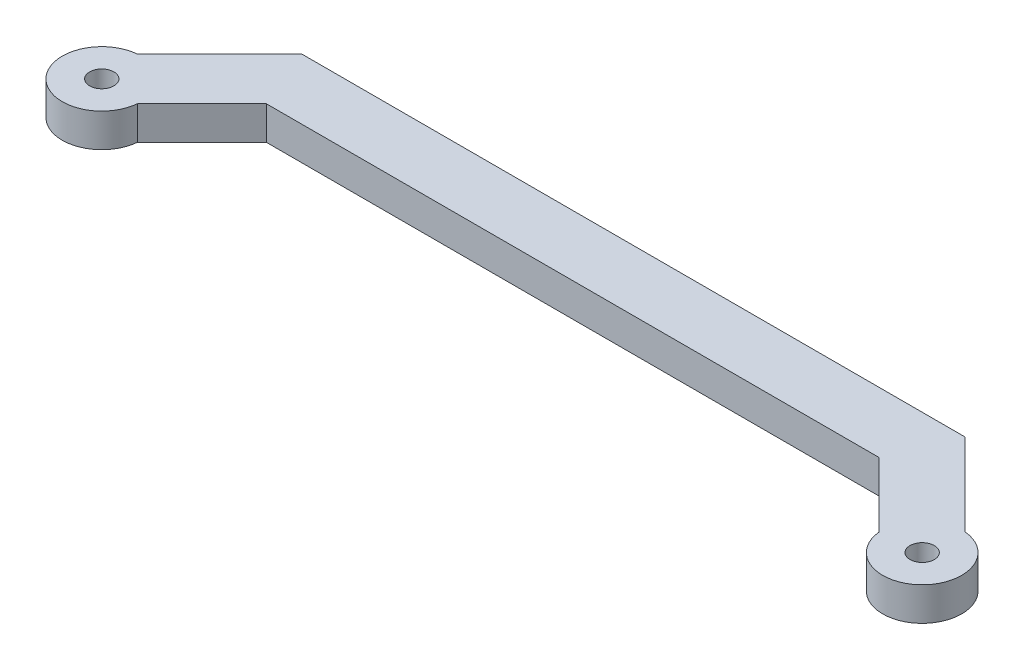
SolidWorks part; units mm, degrees
ref_plane "Plan de face" through (0, 0, 0) normal (0, 0, 1) x (1, 0, 0)
ref_plane "Plan de dessus" through (0, 0, 0) normal (0, 1, 0) x (1, 0, 0)
ref_plane "Plan de droite" through (0, 0, 0) normal (1, 0, 0) x (0, 0, -1)
sketch "Sketch1" plane through (0, 0, 0) normal (0, 1, 0) x (1, 0, 0)
  line L0 (67.5, -10) -> (52.5, 5) construction
  line L1 (52.5, 5) -> (-52.5, 5) construction
  line L2 (0, 5) -> (0, 0) construction
  line L3 (-50.4289, 0) -> (50.4289, 0)
  line L5 (54.5711, 10) -> (-54.5711, 10)
  line L6 (0, 5) -> (0, 0)
  line L7 (50.4289, 0) -> (61.0276, -10.5987)
  line L8 (54.5711, 10) -> (68.0987, -3.5276)
  line L9 (-67.5, -10) -> (-52.5, 5) construction
  line L10 (-54.5711, 10) -> (-68.0987, -3.5276)
  line L11 (-50.4289, 0) -> (-61.0276, -10.5987)
  arc A0 (61.0276, -10.5987) -> (68.0987, -3.5276) centre (67.5, -10) ccw
  circle A1 centre (67.5, -10) radius 2
  circle A2 centre (-67.5, -10) radius 2
  arc A3 (-61.0276, -10.5987) -> (-68.0987, -3.5276) centre (-67.5, -10) cw
  dimension "D5" = 13
  dimension "D6" = 4
  dimension "D1" = 135
  dimension "D3" = 15
  dimension "D4" = 5
  dimension "D7" = 10
  dimension "D10" = 5
  dimension "D8" = 10
  dimension "D2" = 135
extrude "Boss-Extrude1" add sketch "Sketch1" along normal blind 5.5 contours L3 L7 A0 L8 L5 L10 A3 L11 | A2 | A1
equation "\"D10@Sketch1\"=\"D7@Sketch1\"/2"
equation "\"Longueur1\"= 135mm"
equation "\"Longueur2\"= 147mm"
equation "\"D2@Sketch1\"=\"Longueur1\""
